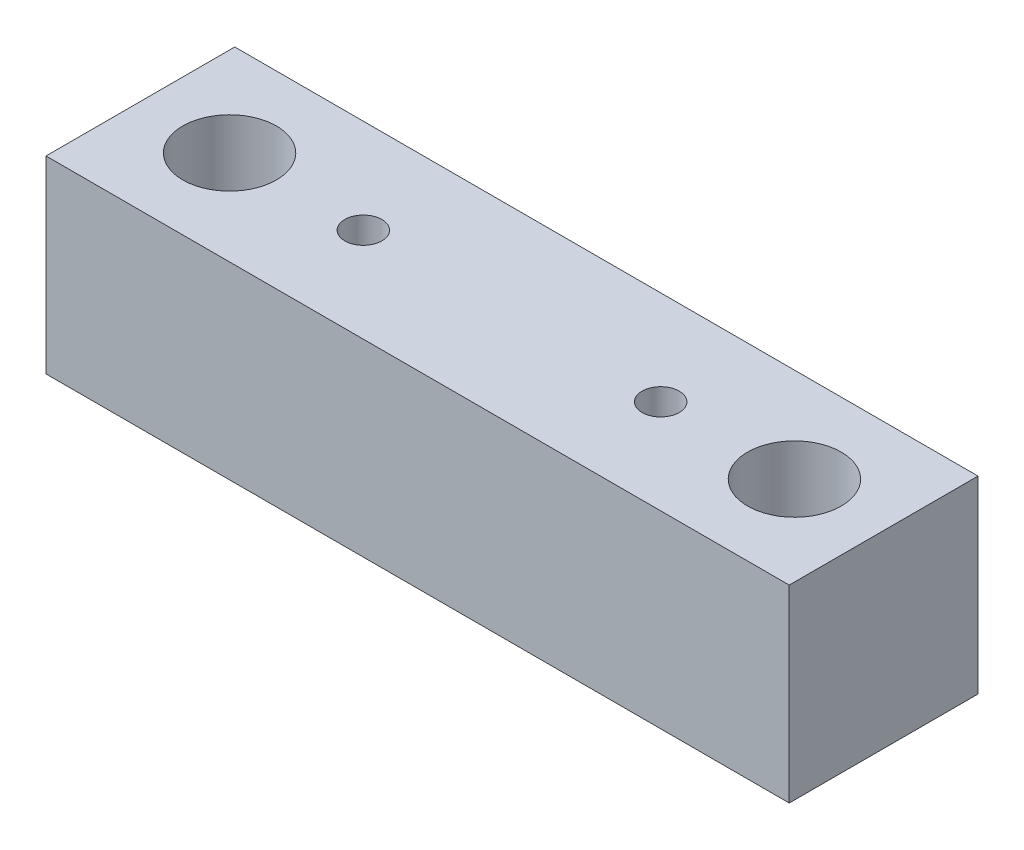
SolidWorks part; units mm, degrees
ref_plane "Front Plane" through (0, 0, 0) normal (0, 0, 1) x (1, 0, 0)
ref_plane "Top Plane" through (0, 0, 0) normal (0, 1, 0) x (1, 0, 0)
ref_plane "Right Plane" through (0, 0, 0) normal (1, 0, 0) x (0, 0, -1)
sketch "Sketch2" plane through (0, 0, 0) normal (0, 1, 0) x (1, 0, 0)
  line L0 (0, 6.35) -> (25, 6.35) construction
  line L1 (0, 0) -> (50, 0)
  line L2 (0, 0) -> (0, 12.7)
  line L3 (0, 12.7) -> (50, 12.7)
  line L6 (25, 12.7) -> (25, 0) construction
  line L7 (50, 0) -> (50, 12.7)
  circle A0 centre (6, 6.35) radius 3.15
  circle A2 centre (15, 6.35) radius 1.25
  circle A4 centre (35, 6.35) radius 1.25
  circle A5 centre (44, 6.35) radius 3.15
  point P9 (0, 0)
  point P10 (0, 0)
  point P19 (0, 0)
  point P20 (0, 0)
  dimension "D3" = 6.3
  dimension "D6" = 2.5
  dimension "D1" = 12.7
  dimension "D2" = 25
  dimension "D4" = 6
  dimension "D5" = 10
extrude "Boss-Extrude1" add sketch "Sketch2" along normal blind 12.7
